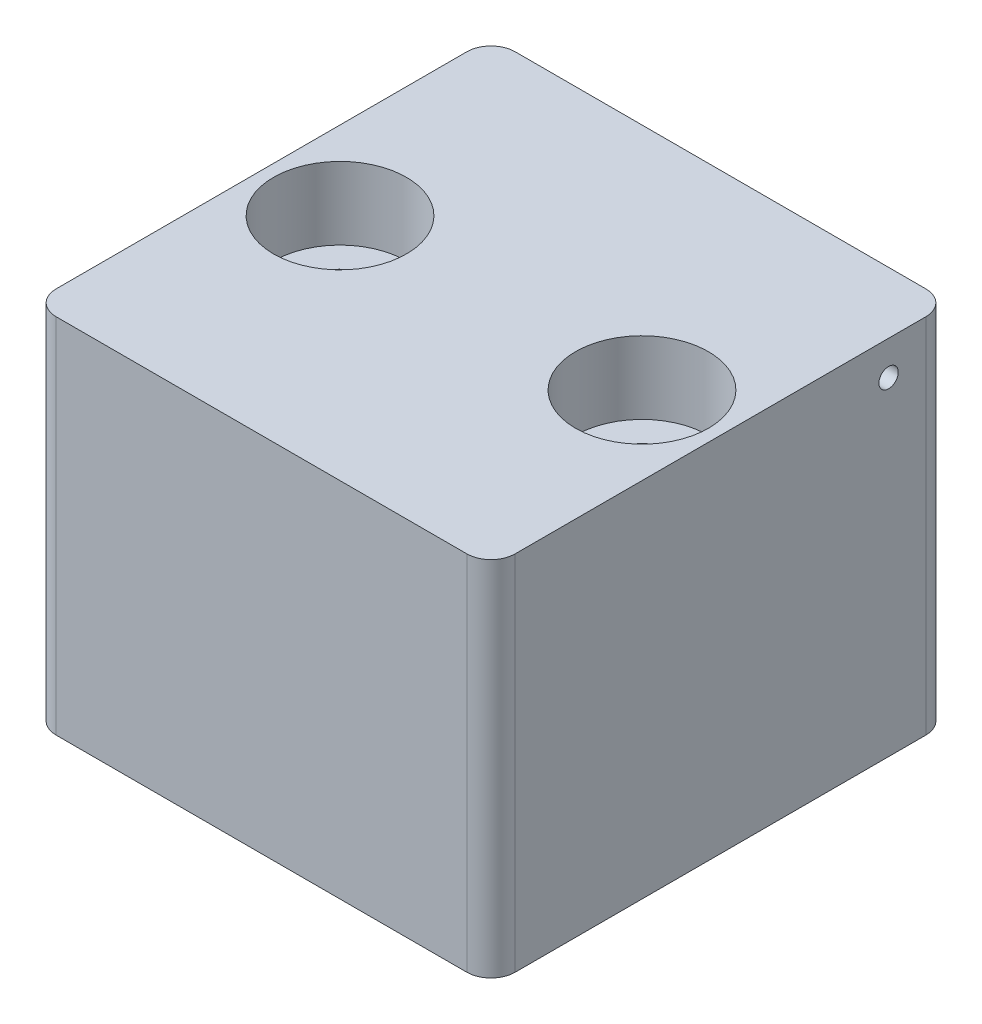
SolidWorks part; units mm, degrees
ref_plane "Front Plane" through (0, 0, 0) normal (0, 0, 1) x (1, 0, 0)
ref_plane "Top Plane" through (0, 0, 0) normal (0, 1, 0) x (1, 0, 0)
ref_plane "Right Plane" through (0, 0, 0) normal (1, 0, 0) x (0, 0, -1)
sketch "Sketch1" plane through (0, 0, 0) normal (0, 1, 0) x (1, 0, 0)
  line L1 (1, 0) -> (18, 0)
  line L2 (0, 1) -> (0, 18)
  line L3 (1, 19) -> (18, 19)
  line L4 (19, 1) -> (19, 18)
  arc A0 (18, 19) -> (19, 18) centre (18, 18) cw
  arc A1 (18, 0) -> (19, 1) centre (18, 1) ccw
  arc A2 (1, 0) -> (0, 1) centre (1, 1) cw
  arc A3 (0, 18) -> (1, 19) centre (1, 18) cw
  point P11 (0, 0)
  point P14 (0, 19)
  dimension "D2" = 1
  dimension "D1" = 19
extrude "Boss-Extrude1" add sketch "Sketch1" along normal blind 15
sketch "Sketch2" plane through (0, 15, 0) normal (0, 1, 0) x (1, 0, 0)
  line L0 (9.5, 19) -> (9.5, 0) construction
  line L1 (3.25, 0) -> (3.25, 19) construction
  line L2 (18, 19) -> (1, 19) construction
  line L3 (1, 0) -> (18, 0) construction
  line L4 (0, 18) -> (0, 1) construction
  circle A0 centre (3.25, 9.5) radius 1.525
  circle A1 centre (15.75, 9.5) radius 1.525
  point P8 (3.25, 9.5)
  dimension "D1" = 3.05
  dimension "D2" = 3.25
extrude "Cut-Extrude1" cut sketch "Sketch2" against normal up to next
sketch "Sketch3" plane through (0, 15, 0) normal (0, 1, 0) x (1, 0, 0)
  circle A0 centre (3.25, 9.5) radius 2.75
  circle A1 centre (15.75, 9.5) radius 2.75
  dimension "D1" = 5.5
extrude "Cut-Extrude2" cut sketch "Sketch3" against normal blind 3
sketch "Sketch4" plane through (0, 0, 0) normal (-1, 0, 0) x (0, 0, 1)
  circle A0 centre (-16.4582, 13.5877) radius 0.4
  point P2 (-16.4582, 13.5877)
  dimension "D1" = 0.8
extrude "Cut-Extrude3" cut sketch "Sketch4" against normal up to next
